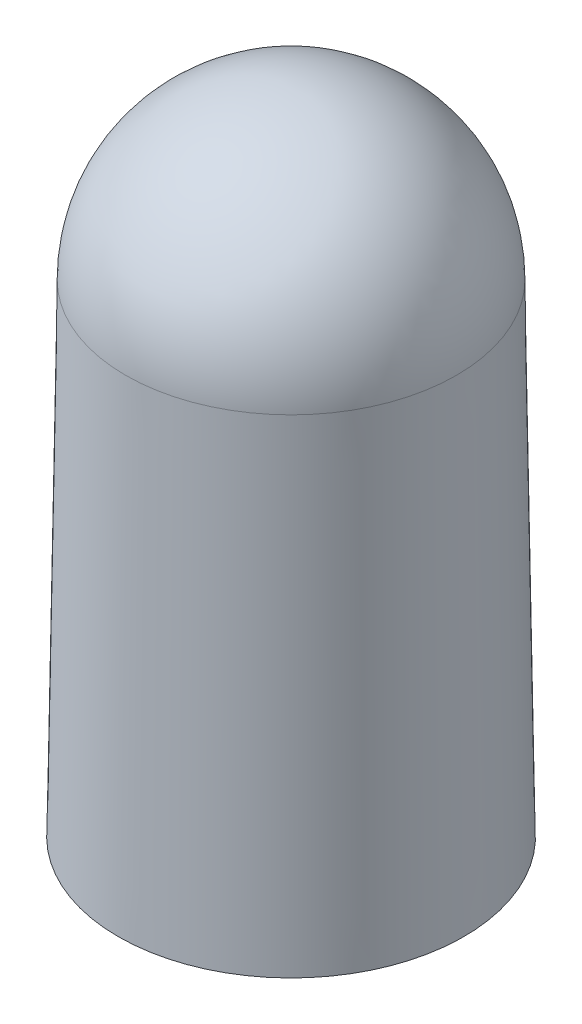
SolidWorks part; units mm, degrees
ref_plane "Front Plane" through (0, 0, 0) normal (0, 0, 1) x (1, 0, 0)
ref_plane "Top Plane" through (0, 0, 0) normal (0, 1, 0) x (1, 0, 0)
ref_plane "Right Plane" through (0, 0, 0) normal (1, 0, 0) x (0, 0, -1)
sketch "Sketch2" plane through (0, 0, 0) normal (0, 0, 1) x (1, 0, 0)
  line L0 (12, 0) -> (12.5375, -35)
  line L1 (10.5, 0) -> (10.5, -35)
  line L2 (10.5, -35) -> (12.5375, -35)
  line L3 (0, 10.5) -> (0, 12)
  line L4 (0, 12) -> (0, -36.1731) construction
  arc A0 (12, 0) -> (0, 12) centre (0, 0) ccw
  arc A1 (10.5, 0) -> (0, 10.5) centre (0, 0) ccw
  dimension "D1" = 24
  dimension "D2" = 21
  dimension "D3" = 35
revolve "Revolve1" add sketch "Sketch2" angle 360 about L4
